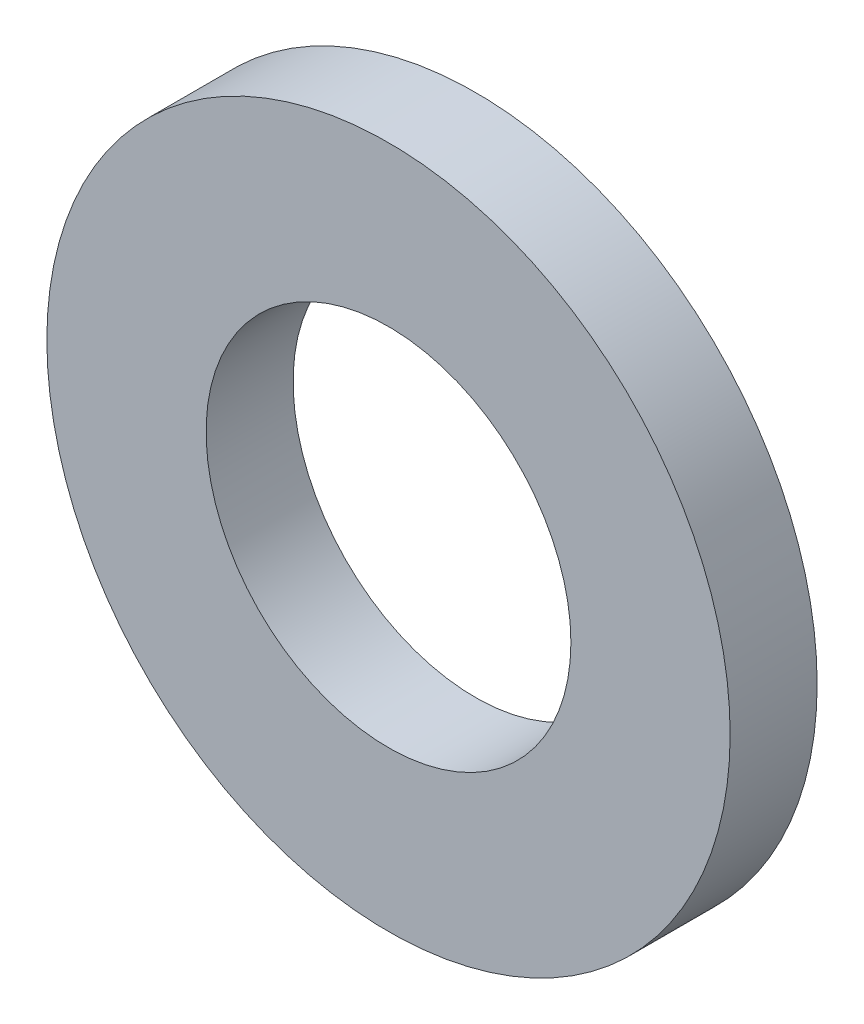
SolidWorks part; units mm, degrees
material "Wrought Stainless Steel"
ref_plane "Front Plane" through (0, 0, 0) normal (0, 0, 1) x (1, 0, 0)
ref_plane "Top Plane" through (0, 0, 0) normal (0, 1, 0) x (1, 0, 0)
ref_plane "Right Plane" through (0, 0, 0) normal (1, 0, 0) x (0, 0, -1)
sketch "Sketch3" plane through (0, 0, 0) normal (0, 0, 1) x (1, 0, 0)
  circle A0 centre (0, 0) radius 6.1849
  circle A1 centre (0, 0) radius 3.302
  dimension "D1" = 12.3698
  dimension "D2" = 6.604
extrude "Boss-Extrude1" add sketch "Sketch3" along normal blind 1.5748
